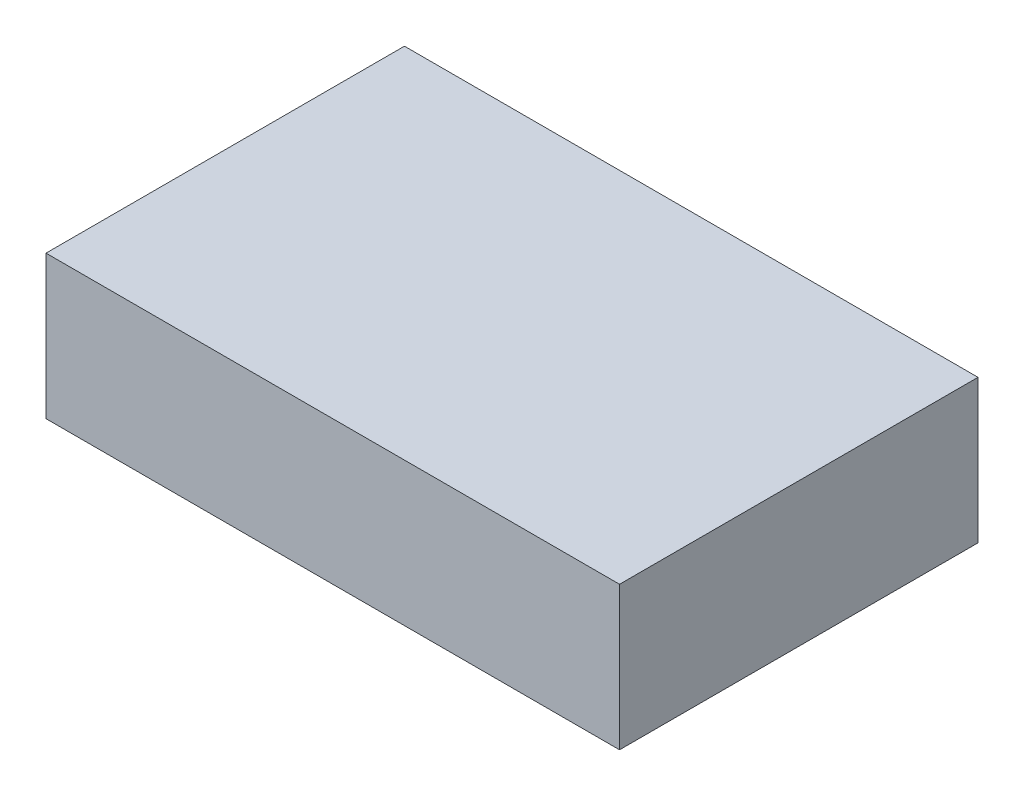
SolidWorks part; units mm, degrees
ref_plane "前视基准面" through (0, 0, 0) normal (0, 0, 1) x (1, 0, 0)
ref_plane "上视基准面" through (0, 0, 0) normal (0, 1, 0) x (1, 0, 0)
ref_plane "右视基准面" through (0, 0, 0) normal (1, 0, 0) x (0, 0, -1)
other "Configuration Table"
sketch "草图1" plane through (0, 0, 0) normal (0, 1, 0) x (1, 0, 0)
  line L1 (0, 0) -> (80, 0)
  line L2 (0, 0) -> (0, -50)
  line L3 (0, -50) -> (80, -50)
  line L4 (80, 0) -> (80, -50)
  dimension "D1" = 50
  dimension "D2" = 80
extrude "凸台-拉伸1" add sketch "草图1" along normal blind 20
